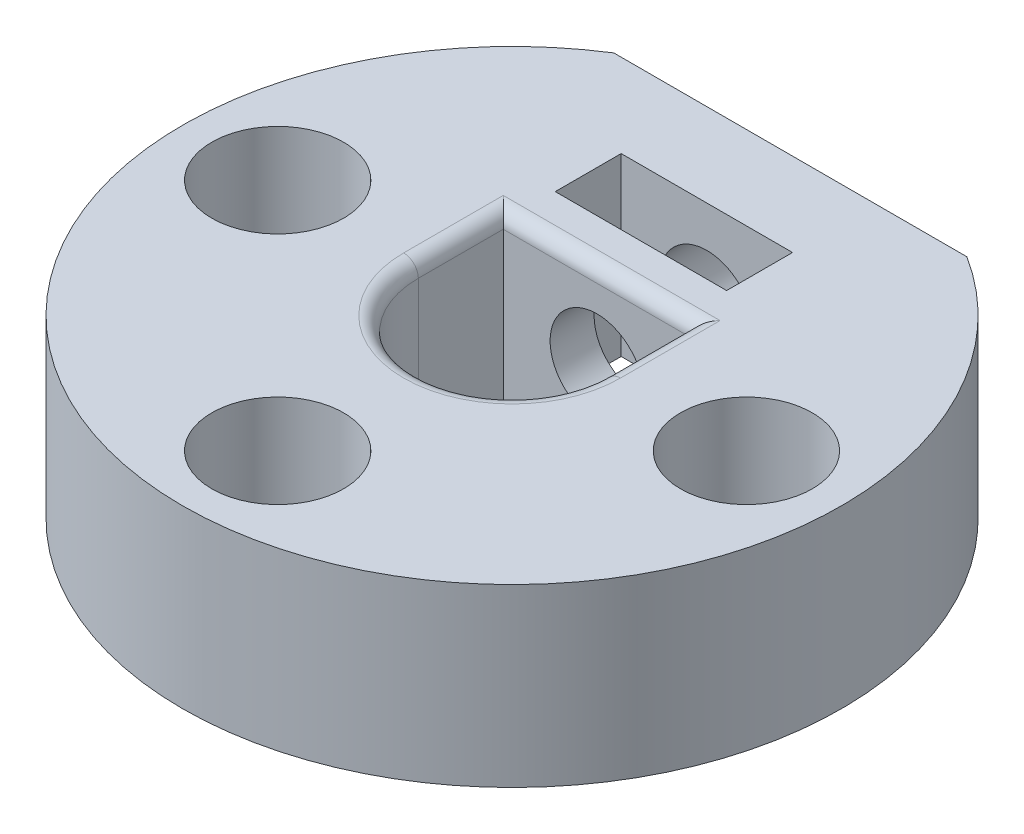
SolidWorks part; units mm, degrees
ref_plane "Plan de face" through (0, 0, 0) normal (0, 0, 1) x (1, 0, 0)
ref_plane "Plan de dessus" through (0, 0, 0) normal (0, 1, 0) x (1, 0, 0)
ref_plane "Plan de droite" through (0, 0, 0) normal (1, 0, 0) x (0, 0, -1)
sketch "Esquisse1" plane through (0, 0, 0) normal (0, 1, 0) x (1, 0, 0)
  line L1 (-3.2, 0) -> (-3.2, 2.9)
  line L2 (3.2, 0) -> (3.2, 2.9)
  line L3 (3.2, 2.9) -> (-3.2, 2.9)
  line L4 (6.026, 9.5) -> (-6.026, 9.5)
  arc A0 (-6.026, 9.5) -> (6.026, 9.5) centre (0, 0) ccw
  arc A1 (-3.2, 0) -> (3.2, 0) centre (0, 0) ccw
  point P10 (0, 2.9)
  dimension "D1" = 22.5
  dimension "D2" = 6.4
  dimension "D3" = 2.9
  dimension "D4" = 9.5
extrude "Boss.-Extru.1" add sketch "Esquisse1" along normal blind 6
hole_wizard "CBORE for M2 SHCS1" positions "Esquisse2" profile "Esquisse3" counterbore size "M2" standard "ANSI Metric" end condition through all
sketch "Esquisse2" plane through (0, 6, 0) normal (0, 1, 0) x (1, 0, 0)
  line L0 (0, 0) -> (6.1221, 0) construction
  line L2 (0, 0) -> (13.3941, 0) construction
  point P0 (8, 0)
  point P28 (-8, 0)
  point P31 (0, 0)
  point P36 (0, -8)
  point P37 (0, 0)
  dimension "D1" = 8
  dimension "D3" = 0
  dimension "D2" = 2
  dimension "D4" = 2
sketch "Esquisse3" plane through (8, 6, 0) normal (1, 0, 0) x (0, 0, 1)
  line L0 (0, 0) -> (0, 6)
  line L1 (0, 6) -> (1.25, 6)
  line L3 (1.25, 6) -> (1.25, 4)
  line L4 (1.25, 4) -> (2.25, 4)
  line L5 (2.25, 4) -> (2.25, 0)
  line L7 (2.25, 0) -> (0, 0)
  line L11 (0, -6.35) -> (0, 107.95) construction
  dimension "Diamètre du perçage jusqu'au prochain" = 2.5
  dimension "Profondeur du perçage jusqu'au prochain" = 6
  dimension "Diamètre du chambrage" = 4.5
  dimension "Profondeur du chambrage" = 4
fillet "Congé1" radius 0.5 4 edges at (0, 6, 3.2) (-3.2, 6, -1.45) (3.2, 6, -1.45) (0, 6, -2.9)
sketch "Esquisse6" plane through (0, 0, 0) normal (0, 0, 1) x (1, 0, 0)
  line L0 (0, 0) -> (0, 6) construction
  line L1 (11.25, 6) -> (-11.25, 6) construction
  line L2 (11.25, 6) -> (-11.25, 6) construction
  circle A0 centre (0, 3) radius 1.6
  dimension "D1" = 3.2
  dimension "D2" = 3
extrude "Enlèv. mat.-Extru.1" cut sketch "Esquisse6" against normal through all
sketch "Esquisse7" plane through (0, 0, 0) normal (0, 1, 0) x (1, 0, 0)
  line L1 (-2.925, 4.4) -> (2.925, 4.4)
  line L2 (-2.925, 4.4) -> (-2.925, 6.65)
  line L3 (-2.925, 6.65) -> (2.925, 6.65)
  line L4 (2.925, 4.4) -> (2.925, 6.65)
  line L5 (-2.925, 4.4) -> (2.925, 6.65) construction
  line L6 (-2.925, 6.65) -> (2.925, 4.4) construction
  line L7 (3.2, 2.9) -> (-3.2, 2.9) construction
  point P0 (0, 5.525)
  dimension "D3" = 1.5
  dimension "D1" = 2.25
  dimension "D2" = 5.85
extrude "Enlèv. mat.-Extru.2" cut sketch "Esquisse7" along normal blind 7.25
sketch "Esquisse8" plane through (0, 0, 0) normal (0, -1, 0) x (1, 0, 0)
  line L0 (-3.2, 0) -> (-3.2, -2.9)
  line L1 (-3.2, -2.9) -> (3.2, -2.9)
  line L2 (3.2, -2.9) -> (3.2, 0)
  line L3 (3.2, -2.9) -> (-3.2, -2.9) construction
  line L4 (0, -3.3) -> (0, 3.3) construction
  line L5 (-3.2, -2.9) -> (-3.2, 0) construction
  arc A0 (3.2, 0) -> (-3.2, 0) centre (0, 0) ccw
  arc A1 (3.2, 0) -> (-3.2, 0) centre (0, 0) ccw construction
  point P14 (0, -2.9)
  point P17 (0, 0)
  point P18 (0, 0)
